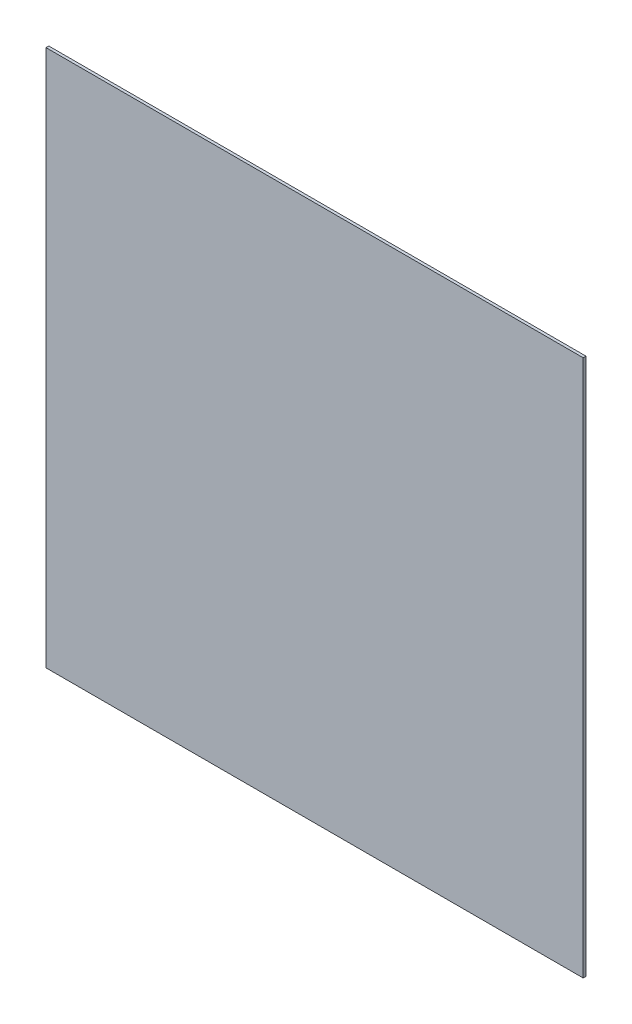
SolidWorks part; units mm, degrees
ref_plane "Front Plane" through (0, 0, 0) normal (0, 0, 1) x (1, 0, 0)
ref_plane "Top Plane" through (0, 0, 0) normal (0, 1, 0) x (1, 0, 0)
ref_plane "Right Plane" through (0, 0, 0) normal (1, 0, 0) x (0, 0, -1)
sketch "Sketch1" plane through (0, 0, 0) normal (0, 0, 1) x (1, 0, 0)
  line L0 (0, 152.4) -> (0, -152.4) construction
  line L1 (-152.4, 0) -> (152.4, 0) construction
  point P0 (0, 152.4)
  point P1 (0, 129.54)
  point P6 (0, 0)
  point P8 (0, -129.54)
  point P9 (-129.54, 0)
  point P11 (152.4, 152.4)
  point P12 (129.54, 0)
  point P13 (-152.4, 152.4)
  point P18 (-152.4, -152.4)
  dimension "D1" = 259.08
  dimension "D2" = 129.54
  dimension "Width" = 304.8
  dimension "Length" = 304.8
sketch "Sketch2" plane through (0, 0, 0) normal (1, 0, 0) x (0, 0, -1)
  line L0 (-0.7937, 152.4) -> (0.7937, 152.4) construction
  point P4 (0, 0)
  dimension "Thickness" = 1.5875
sketch "Sketch3" plane through (0, 0, 0) normal (0, 0, 1) x (1, 0, 0)
  line L0 (-152.4, 0) -> (152.4, 0) construction
  line L5 (152.4, -152.4) -> (-152.4, -152.4)
  line L6 (152.4, -152.4) -> (152.4, 152.4)
  line L7 (152.4, 152.4) -> (-152.4, 152.4)
  line L8 (-152.4, -152.4) -> (-152.4, 152.4)
  line L9 (0, 152.4) -> (0, -152.4) construction
  line L10 (152.4, 0) -> (-152.4, 0) construction
  point P0 (0, 0)
extrude "Boss-Extrude1" add sketch "Sketch3" along normal mid plane 1.5875
equation "\"D1@Boss-Extrude1\"=\"thickness@sketch2\""
equation "\"D1@Sketch1\"=\"Length@Sketch1\"*0.85"
equation "\"D2@Sketch1\"=\"Width@Sketch1\"/2*0.85"
